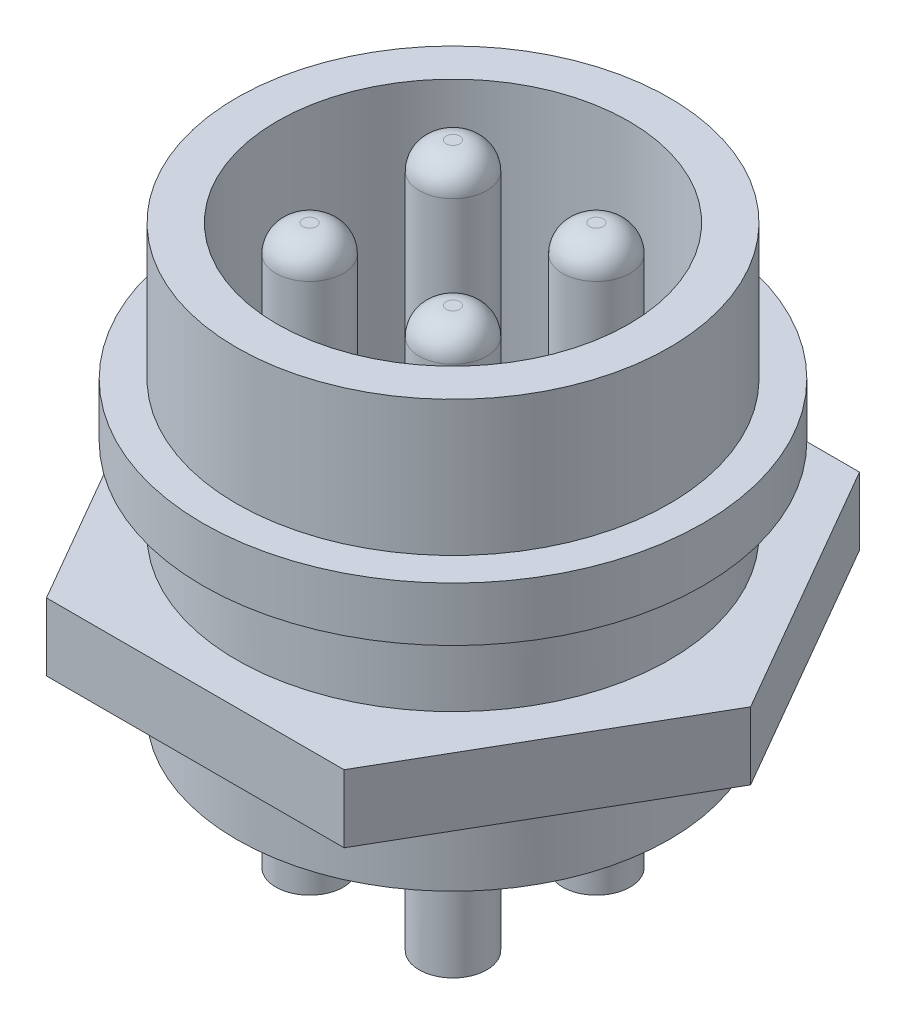
SolidWorks part; units mm, degrees
ref_plane "Płaszczyzna przednia" through (0, 0, 0) normal (0, 0, 1) x (1, 0, 0)
ref_plane "Płaszczyzna górna" through (0, 0, 0) normal (0, 1, 0) x (1, 0, 0)
ref_plane "Płaszczyzna prawa" through (0, 0, 0) normal (1, 0, 0) x (0, 0, -1)
sketch "Szkic1" plane through (0, 0, 0) normal (0, 1, 0) x (1, 0, 0)
  circle A0 centre (-6.1999, 2.6772) radius 8
extrude "Dodanie-wyciągnięcie1" add sketch "Szkic1" along normal blind 15.75
sketch "Szkic2" plane through (0, 15.75, 0) normal (0, 1, 0) x (1, 0, 0)
  circle A0 centre (-6.1999, 2.6772) radius 6.5
extrude "Wytnij-wyciągnięcie1" cut sketch "Szkic2" against normal blind 10
ref_plane "Płaszczyzna1" through (0, 10.75, 0) normal (0, 1, 0) x (1, 0, 0)
sketch "Szkic4" plane through (0, 10.75, 0) normal (0, 1, 0) x (1, 0, 0)
  circle A0 centre (-6.1999, 2.6772) radius 9.25
  circle A1 centre (-6.1999, 2.6772) radius 8
extrude "Dodanie-wyciągnięcie2" add sketch "Szkic4" against normal blind 2
sketch "Szkic5" plane through (0, 0, 0) normal (0, -1, 0) x (1, 0, 0)
  line L0 (-6.1999, 5.3228) -> (-6.1999, -10.6772) construction
  line L1 (-14.1999, -2.6772) -> (1.8001, -2.6772) construction
  line L3 (-8.8499, -0.0272) -> (-3.5499, -0.0272) construction
  line L4 (-8.8499, -0.0272) -> (-8.8499, -5.3272) construction
  line L5 (-8.8499, -5.3272) -> (-3.5499, -5.3272) construction
  line L6 (-3.5499, -0.0272) -> (-3.5499, -5.3272) construction
  line L7 (-8.8499, -0.0272) -> (-3.5499, -5.3272) construction
  line L8 (-8.8499, -5.3272) -> (-3.5499, -0.0272) construction
  circle A0 centre (-6.1999, -2.6772) radius 8 construction
  circle A1 centre (-6.1999, -2.6772) radius 8 construction
  circle A2 centre (-8.8499, -0.0272) radius 1.25
  circle A3 centre (-3.5499, -0.0272) radius 1.25
  circle A4 centre (-3.5499, -5.3272) radius 1.25
  circle A5 centre (-8.8499, -5.3272) radius 1.25
  point P9 (-6.1999, -2.6772)
  dimension "D3" = 2
  dimension "D1" = 5.3
  dimension "D2" = 5.3
  dimension "D4" = 2
extrude "Dodanie-wyciągnięcie3" add sketch "Szkic5" along normal blind 4.9 and the other way up to surface other way up to face at (-6.1999, 15.75, 3.8228)
fillet "Zaokrąglenie1" radius 1 4 edges at (-8.8499, 15.75, 1.2228) (-8.8499, 15.75, -4.0772) (-3.5499, 15.75, 1.2228) (-3.5499, 15.75, -4.0772)
ref_plane "Płaszczyzna2" through (0, 5.75, 0) normal (0, -1, 0) x (-1, 0, 0)
sketch "Szkic6" plane through (0, 5.75, 0) normal (0, -1, 0) x (-1, 0, 0)
  line L1 (17.2023, 2.6772) -> (11.7011, 12.2056)
  line L2 (11.7011, 12.2056) -> (0.6988, 12.2056)
  line L3 (0.6988, 12.2056) -> (-4.8024, 2.6772)
  line L4 (-4.8024, 2.6772) -> (0.6988, -6.8511)
  line L5 (0.6988, -6.8511) -> (11.7011, -6.8511)
  line L6 (11.7011, -6.8511) -> (17.2023, 2.6772)
  circle A0 centre (6.1999, 2.6772) radius 8
  circle A1 centre (6.1999, 2.6772) radius 9.5283 construction
extrude "Dodanie-wyciągnięcie4" add sketch "Szkic6" along normal blind 2.5
